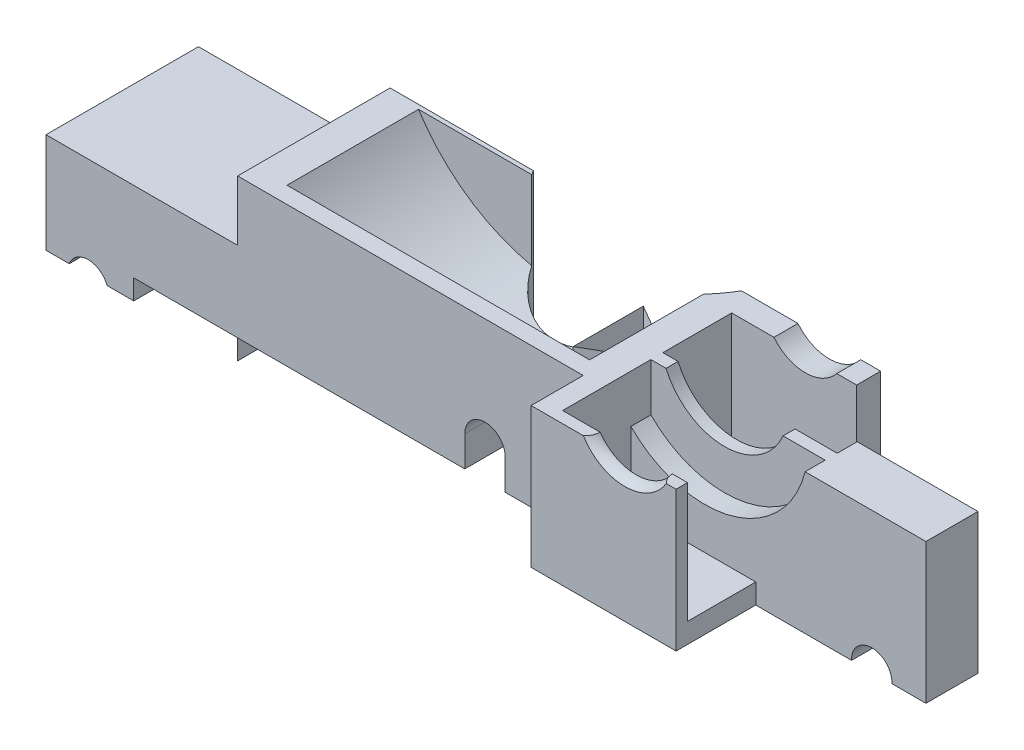
SolidWorks part; units mm, degrees
ref_plane "Front Plane" through (0, 0, 0) normal (0, 0, 1) x (1, 0, 0)
ref_plane "Top Plane" through (0, 0, 0) normal (0, 1, 0) x (1, 0, 0)
ref_plane "Right Plane" through (0, 0, 0) normal (1, 0, 0) x (0, 0, -1)
sketch "Sketch1" plane through (0, 0, 0) normal (0, 1, 0) x (1, 0, 0)
  line L1 (0, 0) -> (419.1, 0)
  line L2 (0, 0) -> (0, 142.1841)
  line L3 (0, 142.1841) -> (419.1, 142.1841)
  line L4 (419.1, 0) -> (419.1, 142.1841)
  dimension "D1" = 419.1
  dimension "D2" = 142.1841
extrude "Boss-Extrude1" add sketch "Sketch1" along normal blind 88.9
ref_plane "Plane1" through (0, 0, -134.333) normal (0, 0, -1) x (-1, 0, 0)
ref_plane "Plane2" through (0, 0, -67.8332) normal (0, 0, -1) x (-1, 0, 0)
ref_plane "Plane3" through (0, 0, -14.4831) normal (0, 0, -1) x (-1, 0, 0)
ref_plane "Plane4" through (0, 0, -131.633) normal (0, 0, -1) x (-1, 0, 0)
sketch "Sketch2" plane through (0, 0, -131.633) normal (0, 0, -1) x (-1, 0, 0)
  circle A0 centre (-116.7166, 150.0612) radius 119.38
  arc A1 (-20.1165, 209.6486) -> (-213.3168, 90.4738) centre (-116.7166, 150.0612) ccw construction
  dimension "D1" = 238.76
sketch "Sketch3" plane through (0, 0, -134.333) normal (0, 0, -1) x (-1, 0, 0)
  line L0 (-116.7166, 150.0612) -> (-278.6494, 104.852) construction
  circle A0 centre (-278.6494, 104.852) radius 24.9999
sketch "Sketch4" plane through (0, 0, -67.8332) normal (0, 0, -1) x (-1, 0, 0)
  circle A0 centre (-278.6494, 104.852) radius 40.386
  dimension "D1" = 80.772
sketch "Sketch5" plane through (0, 0, -14.4831) normal (0, 0, -1) x (-1, 0, 0)
  circle A0 centre (-278.6494, 104.852) radius 27.686
  dimension "D1" = 55.372
sketch "Sketch6" plane through (0, 88.9, 0) normal (0, 1, 0) x (1, 0, 0)
  line L0 (278.6494, 14.4831) -> (278.6494, 7.1425) construction
  line L1 (306.3354, 14.4831) -> (250.9634, 14.4831) construction
  line L2 (278.6494, 67.8332) -> (278.6494, 60.2336) construction
  line L3 (319.0354, 67.8332) -> (238.2634, 67.8332) construction
  line L4 (278.6494, 134.333) -> (278.6494, 119.093) construction
  line L5 (303.6493, 134.333) -> (253.6494, 134.333) construction
  dimension "D1" = 7.3406
  dimension "D2" = 7.5997
  dimension "D3" = 15.24
extrude "Cut-Extrude1" cut sketch "Sketch2" against normal blind 83.4009
sketch "Sketch7" plane through (0, 88.9, 0) normal (0, 1, 0) x (1, 0, 0)
  line L0 (419.1, 0) -> (419.1, 142.1841) construction
  line L1 (419.1, 119.093) -> (231.9393, 119.093)
  line L2 (419.1, 119.093) -> (419.1, 88.1532)
  line L3 (419.1, 55.1332) -> (231.9393, 55.1332)
  line L4 (231.9393, 119.093) -> (231.9393, 88.1532)
  line L11 (219.2393, 131.633) -> (219.2393, 48.2321) construction
  line L12 (231.9393, 88.1532) -> (419.1, 88.1532)
  line L13 (419.1, 55.1332) -> (419.1, 11.8466)
  line L14 (231.9393, 55.1332) -> (231.9393, 11.8466)
  line L15 (231.9393, 11.8466) -> (419.1, 11.8466)
  dimension "D1" = 12.7
  dimension "D2" = 33.02
  dimension "D3" = 43.2867
  dimension "D4" = 30.9397
extrude "Cut-Extrude2" cut sketch "Sketch7" against normal through all
extrude "Cut-Extrude4" cut sketch "Sketch4" along normal blind 7.62
ref_axis "Axis1" through (278.6494, 104.852, -328.4565) along (0, 0, 1)
sketch "Sketch39" plane through (0, 0, -55.1332) normal (0, 0, 1) x (1, 0, 0)
  line L0 (231.9393, 0) -> (231.9393, 88.9) construction
  line L1 (419.1, 88.9) -> (231.9393, 88.9) construction
  line L2 (0, 88.9) -> (419.1, 88.9) construction
  line L3 (231.9393, 58.5274) -> (231.9393, 88.9)
  line L4 (231.9393, 88.9) -> (342.472, 88.9)
  arc A0 (231.9393, 58.5274) -> (342.472, 88.9) centre (278.6494, 104.852) ccw
  arc A1 (241.5473, 88.9) -> (315.7514, 88.9) centre (278.6494, 104.852) ccw construction
  dimension "D1" = 25.4
extrude "Cut-Extrude17" cut sketch "Sketch39" along normal up to surface (12.7 mm away)
sketch "Sketch40" plane through (0, 0, -88.1532) normal (0, 0, -1) x (-1, 0, 0)
  line L0 (-231.9393, 88.9) -> (-231.9393, 58.5274)
  line L1 (-231.9393, 88.9) -> (-342.472, 88.9)
  arc A0 (-231.9393, 58.5274) -> (-342.472, 88.9) centre (-278.6494, 104.852) cw
  arc A1 (-342.472, 88.9) -> (-231.9393, 58.5274) centre (-278.6494, 104.852) ccw construction
extrude "Cut-Extrude18" cut sketch "Sketch40" against normal up to surface (12.7 mm away) up to face at (278.6494, 76.683, -75.4532)
sketch "Sketch18" plane through (0, 0, -142.1841) normal (0, 0, -1) x (-1, 0, 0)
  circle A0 centre (-278.6494, 104.852) radius 25.527
  dimension "D1" = 51.054
extrude "Cut-Extrude11" cut sketch "Sketch18" against normal up to surface (23.0911 mm away) up to face at (325.5196, 44.45, -119.093)
sketch "Sketch8" plane through (0, 0, -142.1841) normal (0, 0, -1) x (-1, 0, 0)
  line L1 (-419.1, 88.9) -> (0, 88.9)
  line L2 (-419.1, 88.9) -> (-419.1, 0)
  line L3 (-419.1, 0) -> (0, 0)
  line L4 (0, 88.9) -> (0, 0)
extrude "Cut-Extrude6" cut sketch "Sketch8" against normal up to vertex (7.8511 mm away) up to point (278.6494, 88.9, -134.333)
sketch "Sketch9" plane through (0, 0, 0) normal (0, 0, 1) x (1, 0, 0)
  line L1 (0, 88.9) -> (419.1, 88.9)
  line L2 (0, 88.9) -> (0, 0)
  line L3 (0, 0) -> (419.1, 0)
  line L4 (419.1, 88.9) -> (419.1, 0)
extrude "Cut-Extrude7" cut sketch "Sketch9" against normal up to vertex (7.1425 mm away) up to point (278.6494, 88.9, -7.1425)
sketch "Sketch10" plane through (0, 0, -7.1425) normal (0, 0, 1) x (1, 0, 0)
  line L0 (0, 0) -> (419.1, 0) construction
  line L1 (0, 88.9) -> (219.202, 88.9)
  line L2 (0, 88.9) -> (0, 0)
  line L3 (0, 0) -> (219.202, 0)
  line L4 (219.202, 88.9) -> (219.202, 0)
  dimension "D1" = 219.202
extrude "Cut-Extrude8" cut sketch "Sketch10" against normal blind 30.48
sketch "Sketch12" plane through (0, 0, 0) normal (0, -1, 0) x (1, 0, 0)
  line L5 (0, -37.6225) -> (-121.5336, -37.6225)
  line L6 (0, -37.6225) -> (0, -134.333)
  line L7 (0, -134.333) -> (-121.5336, -134.333)
  line L8 (-121.5336, -37.6225) -> (-121.5336, -134.333)
  line L9 (0, -85.9777) -> (53.0931, -85.9777) construction
  line L10 (0, -134.333) -> (0, -37.6225) construction
  line L11 (0, -37.6225) -> (219.202, -37.6225) construction
  point P9 (0, -85.9777)
  dimension "D1" = 121.5336
extrude "Boss-Extrude2" add sketch "Sketch12" against normal blind 50.8
sketch "Sketch14" plane through (0, 0, 0) normal (0, -1, 0) x (1, 0, 0)
  line L0 (419.1, -134.333) -> (-121.5336, -134.333) construction
  line L1 (-121.5336, -37.6225) -> (-65.8865, -37.6225)
  line L2 (-121.5336, -37.6225) -> (-121.5336, -134.333)
  line L3 (-121.5336, -134.333) -> (-65.8865, -134.333)
  line L4 (-65.8865, -37.6225) -> (-65.8865, -134.333)
extrude "Boss-Extrude3" add sketch "Sketch14" along normal blind 12.7
sketch "Sketch17" plane through (0, 0, -134.333) normal (0, 0, -1) x (-1, 0, 0)
  line L0 (-169.736, 19.3164) -> (-169.736, 0)
  line L1 (-419.1, 0) -> (65.8865, 0) construction
  line L2 (-169.736, 0) -> (-144.082, 0)
  line L3 (-144.082, 0) -> (-144.082, 19.3164)
  circle A0 centre (-384.7359, 0.5319) radius 12.827
  arc A1 (-144.082, 19.3164) -> (-169.736, 19.3164) centre (-156.909, 19.3164) ccw
  circle A2 centre (94.7989, -17.274) radius 12.827
  dimension "D1" = 25.654
  dimension "D2" = 25.654
  dimension "D3" = 25.654
extrude "Cut-Extrude10" cut sketch "Sketch17" against normal up to surface (127.1905 mm away) up to face at (319.151, 44.45, -7.1425)
sketch "Sketch20" plane through (0, 0, -11.8466) normal (0, 0, -1) x (-1, 0, 0)
  line L0 (-419.1, 88.9) -> (-419.1, 0) construction
  line L1 (-419.1, 88.9) -> (-406.4, 88.9)
  line L2 (-419.1, 88.9) -> (-419.1, 50.8)
  line L3 (-419.1, 50.8) -> (-406.4, 50.8)
  line L4 (-406.4, 88.9) -> (-406.4, 50.8)
  line L5 (-419.1, 0) -> (-397.5519, 0) construction
  line L6 (-298.5783, 88.9) -> (-419.1, 88.9) construction
  dimension "D1" = 50.8
  dimension "D3" = 12.7
extrude "Boss-Extrude4" [suppressed] add sketch "Sketch20" along normal up to surface (122.4864 mm away)
sketch "Sketch22" plane through (0, 0, -7.1425) normal (0, 0, 1) x (1, 0, 0)
  line L1 (219.202, 0) -> (419.1, 0)
  line L2 (219.202, 0) -> (219.202, 88.9)
  line L3 (219.202, 88.9) -> (419.1, 88.9)
  line L4 (419.1, 0) -> (419.1, 88.9)
extrude "Boss-Extrude5" add sketch "Sketch22" along normal blind 2.54
sketch "Sketch29" plane through (0, 0, -7.1425) normal (0, 0, -1) x (-1, 0, 0)
  circle A4 centre (-384.7359, 0.5319) radius 12.827
  arc A5 (-371.92, 0) -> (-397.5519, 0) centre (-384.7359, 0.5319) ccw construction
extrude "Cut-Extrude14" cut sketch "Sketch29" against normal through all
sketch "Sketch30" plane through (0, 0, -134.333) normal (0, 0, -1) x (-1, 0, 0)
  line L0 (-14.194, 88.9) -> (-20.7587, 88.9)
  line L1 (0, 88.9) -> (-258.7205, 88.9) construction
  line L2 (-212.6746, 88.9) -> (-219.2393, 88.9)
  arc A0 (-219.2393, 88.9) -> (-14.194, 88.9) centre (-116.7166, 150.0612) ccw
  arc A1 (-219.2393, 88.9) -> (-14.194, 88.9) centre (-116.7166, 150.0612) ccw construction
  arc A2 (-212.6746, 88.9) -> (-20.7587, 88.9) centre (-116.7166, 150.0612) ccw
  dimension "D1" = 227.584
extrude "Boss-Extrude6" add sketch "Sketch30" against normal up to surface (86.1009 mm away) contours A2 L0 A0 L2 up to face at (116.7166, 59.7906, -48.2321)
ref_plane "Plane7" through (0, 104.852, 0) normal (0, 1, 0) x (1, 0, 0)
sketch "Sketch44" plane through (0, 104.852, 0) normal (0, 1, 0) x (1, 0, 0)
  line L0 (231.9393, 11.8466) -> (419.1, 11.8466) construction
  line L1 (278.6494, 11.8466) -> (306.5894, 11.8466)
  line L2 (278.6494, 11.8466) -> (278.6494, 4.6025)
  line L3 (278.6494, 4.6025) -> (309.3834, 4.6025)
  line L5 (278.6494, 328.4565) -> (278.6494, -18.2896) construction
  line L7 (419.1, 4.6025) -> (219.202, 4.6025) construction
  arc A0 (306.5894, 11.8466) -> (309.3834, 4.6025) centre (317.3773, 11.8466) ccw
  point P11 (0, 0)
  point P12 (0, 0)
  dimension "D1" = 27.94
  dimension "D2" = 30.734
revolve "Cut-Revolve1" cut sketch "Sketch44" angle 360 about axis through (278.6494, 104.852, -328.4565) along (0, 0, 1)
sketch "Sketch45" plane through (0, 88.9, 0) normal (0, 1, 0) x (1, 0, 0)
  line L0 (419.1, 4.6025) -> (304.9193, 4.6025) construction
  line L1 (419.1, 55.1332) -> (311.15, 55.1332)
  line L2 (419.1, 55.1332) -> (419.1, 4.6025)
  line L3 (419.1, 4.6025) -> (311.15, 4.6025)
  line L4 (311.15, 55.1332) -> (311.15, 4.6025)
  line L5 (298.5783, 134.333) -> (419.1, 134.333) construction
  line L6 (311.15, 134.333) -> (419.1, 134.333)
  line L7 (311.15, 134.333) -> (311.15, 119.093)
  line L8 (311.15, 119.093) -> (419.1, 119.093)
  line L9 (419.1, 134.333) -> (419.1, 119.093)
  dimension "D1" = 107.95
extrude "Cut-Extrude22" cut sketch "Sketch45" against normal through all
sketch "Sketch46" plane through (0, 0, 0) normal (0, -1, 0) x (1, 0, 0)
  line L0 (219.202, -4.6025) -> (311.15, -4.6025) construction
  line L1 (219.202, -4.6025) -> (311.15, -4.6025)
  line L2 (219.202, -4.6025) -> (219.202, -134.333)
  line L3 (219.202, -134.333) -> (311.15, -134.333)
  line L4 (311.15, -4.6025) -> (311.15, -134.333)
  line L5 (311.15, -134.333) -> (169.736, -134.333) construction
  line L6 (311.15, -119.093) -> (311.15, -134.333) construction
  line L7 (219.202, -37.6225) -> (219.202, -4.6025) construction
extrude "Boss-Extrude7" add sketch "Sketch46" against normal blind 12.7
sketch "Sketch47" plane through (0, 88.9, 0) normal (0, 1, 0) x (1, 0, 0)
  line L0 (0, 134.333) -> (258.7205, 134.333) construction
  line L1 (222.9002, 134.333) -> (90.9179, 134.333)
  line L5 (169.736, 134.333) -> (144.082, 134.333) construction
  arc A1 (222.9002, 134.333) -> (90.9179, 134.333) centre (156.909, 172.433) cw
  point P3 (156.909, 134.333)
  point P6 (112.4889, 134.333)
  point P7 (206.4297, 134.333)
  dimension "D1" = 76.2
  dimension "D2" = 38.1
extrude "Cut-Extrude23" cut sketch "Sketch47" against normal through all
sketch "Sketch48" plane through (0, 88.9, 0) normal (0, 1, 0) x (1, 0, 0)
  line L0 (219.202, 37.6225) -> (219.202, 61.321)
  line L1 (219.202, 83.774) -> (219.202, 128.5465)
  line L2 (200.152, 94.7725) -> (200.152, 50.3225)
  line L3 (200.152, 50.3225) -> (219.202, 61.321)
  line L4 (200.152, 94.7725) -> (219.202, 83.774)
  line L6 (219.202, 37.6225) -> (0, 37.6225) construction
  arc A0 (212.6746, 120.5038) -> (222.9002, 134.333) centre (156.909, 172.433) ccw construction
  point P7 (0, 0)
  point P8 (219.202, 128.5465)
  point P10 (200.152, 98.3422)
  point P11 (218.1788, 134.333)
  dimension "D1" = 60
  dimension "D2" = 44.45
  dimension "D3" = 19.05
  dimension "D4" = 12.7
surface "Surface-Extrude3" sketch "Sketch48"
sketch "Sketch32" plane through (0, -12.7, 0) normal (0, -1, 0) x (1, 0, 0)
  line L0 (0, -37.6225) -> (0, -71.5763)
  line L1 (-65.8865, -37.6225) -> (144.082, -37.6225) construction
  line L2 (90.9179, -134.333) -> (-65.8865, -134.333) construction
  line L3 (31.8968, -85.9777) -> (94.1966, -85.9777) construction
  line L4 (0, -71.5763) -> (19.05, -60.5777)
  line L5 (19.05, -60.5777) -> (19.05, -111.3777)
  line L6 (19.05, -111.3777) -> (0, -100.3792)
  line L7 (0, -100.3792) -> (0, -134.333)
  point P14 (19.05, -85.9777)
  dimension "D1" = 60
  dimension "D2" = 19.05
  dimension "D3" = 50.8
surface "Surface-Extrude1" sketch "Sketch32"
